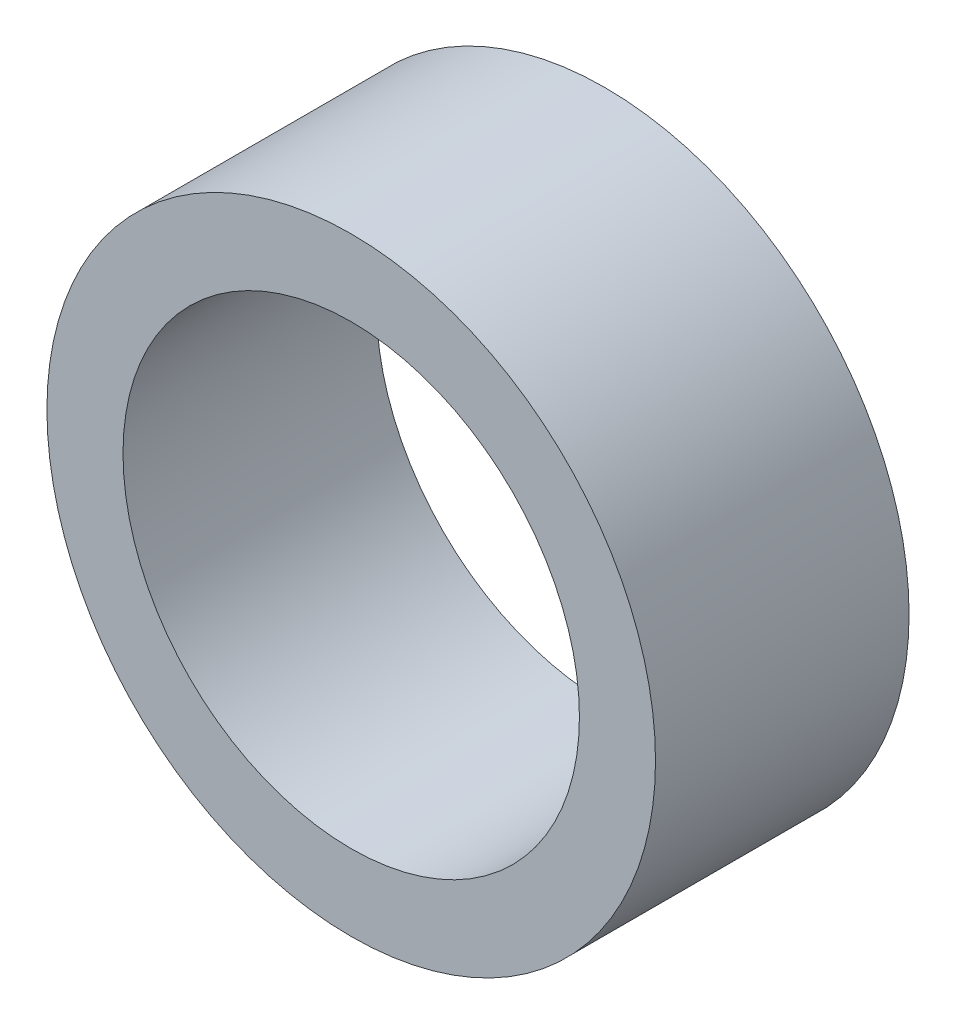
SolidWorks part; units mm, degrees
ref_plane "Plan de face" through (0, 0, 0) normal (0, 0, 1) x (1, 0, 0)
ref_plane "Plan de dessus" through (0, 0, 0) normal (0, 1, 0) x (1, 0, 0)
ref_plane "Plan de droite" through (0, 0, 0) normal (1, 0, 0) x (0, 0, -1)
sketch "Esquisse1" plane through (0, 0, 0) normal (0, 0, 1) x (1, 0, 0)
  circle A0 centre (0, 0) radius 6
  dimension "D1" = 12
extrude "Boss.-Extru.1" add sketch "Esquisse1" along normal blind 5
sketch "Esquisse2" plane through (0, 0, 5) normal (0, 0, 1) x (1, 0, 0)
  circle A0 centre (0, 0) radius 4.5
  dimension "D1" = 9
extrude "Enlèv. mat.-Extru.1" cut sketch "Esquisse2" against normal through all
